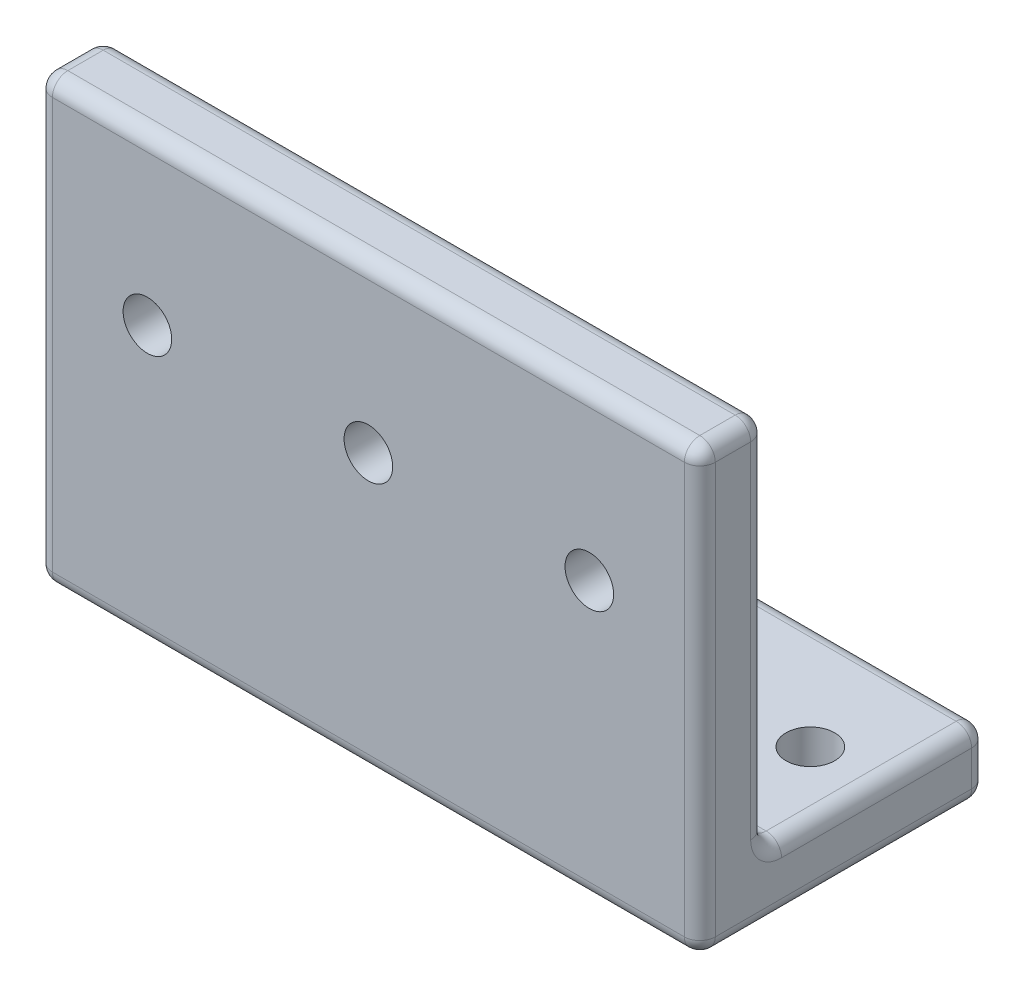
SolidWorks part; units mm, degrees
ref_plane "前视基准面" through (0, 0, 0) normal (0, 0, 1) x (1, 0, 0)
ref_plane "上视基准面" through (0, 0, 0) normal (0, 1, 0) x (1, 0, 0)
ref_plane "右视基准面" through (0, 0, 0) normal (1, 0, 0) x (0, 0, -1)
other "Configuration Table"
sketch "草图1" plane through (0, 0, 0) normal (0, 0, 1) x (1, 0, 0)
  line L0 (55, 0) -> (-55, 0) construction
  line L1 (-8, 3) -> (8, 3)
  line L2 (-8, 3) -> (-8, 0)
  line L3 (-8, 0) -> (8, 0)
  line L4 (8, 3) -> (8, 0)
  line L5 (0, -55) -> (0, 55) construction
  dimension "D1" = 16
  dimension "D2" = 8
  dimension "D3" = 3
extrude "凸台-拉伸1" add sketch "草图1" against normal blind 10
sketch "草图2" plane through (0, 0, 0) normal (0, 0, 1) x (1, 0, 0)
  line L0 (5.5, 0) -> (-5.5, 0) construction
  line L1 (8, 0) -> (-22, 0)
  line L2 (8, 0) -> (8, 20)
  line L3 (8, 20) -> (-22, 20)
  line L4 (-22, 0) -> (-22, 20)
  line L5 (8, 0) -> (8, 3) construction
  dimension "D1" = 30
  dimension "D2" = 20
extrude "凸台-拉伸2" add sketch "草图2" along normal blind 3
hole_wizard "Ø2.2 (2.2) 直径孔1" positions "草图3" profile "草图4" hole size "Ø2.2" standard "ANSI Metric" end condition up to next
sketch "草图3" plane through (0, 3, 0) normal (0, 1, 0) x (1, 0, 0)
  line L0 (8, 0) -> (-8, 0) construction
  line L2 (-8, 10) -> (-8, 0) construction
  point P0 (-5, 5)
  point P2 (5, 5)
  dimension "D1" = 5
  dimension "D2" = 10
  dimension "D3" = 3
  dimension "D4" = 5
sketch "草图4" plane through (-5, 3, -5) normal (1, 0, 0) x (0, 0, 1)
  line L0 (0, 0) -> (0, 3)
  line L1 (0, 3) -> (1.1, 3)
  line L2 (1.1, 3) -> (1.1, 0)
  line L5 (1.1, 0) -> (0, 0)
  line L11 (0, -6.35) -> (0, 107.95) construction
  dimension "通孔孔直径" = 2.2
  dimension "通孔孔深度" = 3
hole_wizard "Ø2.2 (2.2) 直径孔2" positions "草图7" profile "草图8" hole size "Ø2.2" standard "ANSI Metric" end condition up to next
sketch "草图7" plane through (0, 0, 3) normal (0, 0, 1) x (1, 0, 0)
  line L0 (7.15, 0) -> (-7.15, 0) construction
  line L1 (-22, 20) -> (-22, 0) construction
  point P0 (-17, 12.52)
  point P2 (-7, 12.52)
  point P8 (3, 12.52)
  dimension "D1" = 12.52
  dimension "D2" = 12.52
  dimension "D3" = 5
  dimension "D4" = 15
  dimension "D5" = 12.52
  dimension "D6" = 25
sketch "草图8" plane through (-17, 12.52, 3) normal (1, 0, 0) x (0, -1, 0)
  line L0 (0, 0) -> (0, 3)
  line L1 (0, 3) -> (1.1, 3)
  line L2 (1.1, 3) -> (1.1, 0)
  line L5 (1.1, 0) -> (0, 0)
  line L11 (0, -6.35) -> (0, 107.95) construction
  dimension "通孔孔直径" = 2.2
  dimension "通孔孔深度" = 3
fillet "圆角1" radius 0.7 21 edges at (-7, 0, 3) (-22, 20, 1.5) (-22, 0, 1.5) (-15, 0, 0) (-8, 1.5, 0) (-8, 0, -5) (-22, 10, 0) (-7, 20, 3) (-7, 20, 0) (8, 20, 1.5) (8, 11.5, 0) (-22, 10, 3) (8, 10, 3) (8, 0, -3.5) (-8, 3, -5) (-8, 1.5, -10) (0, 0, -10) (8, 1.5, -10) (0, 3, -10) (0, 3, 0) (8, 3, -5)
